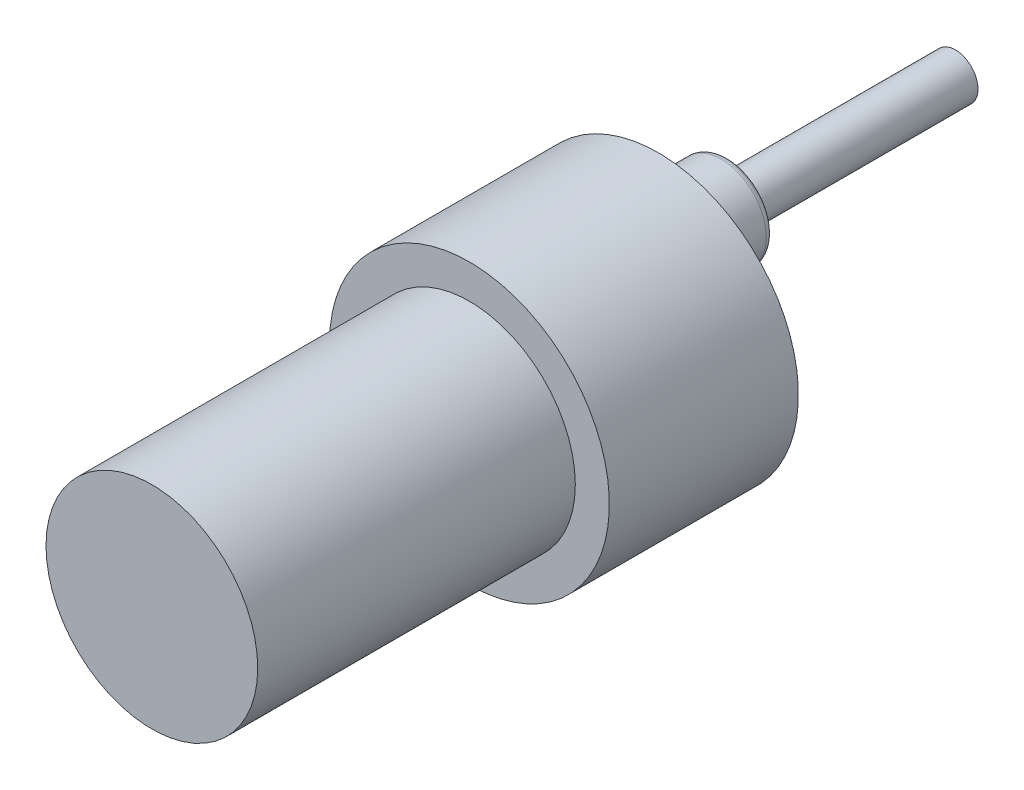
SolidWorks part; units mm, degrees
ref_plane "Front Plane" through (0, 0, 0) normal (0, 0, 1) x (1, 0, 0)
ref_plane "Top Plane" through (0, 0, 0) normal (0, 1, 0) x (1, 0, 0)
ref_plane "Right Plane" through (0, 0, 0) normal (1, 0, 0) x (0, 0, -1)
ref_plane "Plane1" through (0, 0, 0) normal (0, -1, 0) x (1, 0, 0)
sketch "Sketch1" plane through (0, 0, 0) normal (0, -1, 0) x (1, 0, 0)
  line L0 (18.5, 0) -> (0, 0)
  line L1 (0, 0) -> (0, -25)
  line L2 (0, -25) -> (18.5, -25)
  line L3 (18.5, -25) -> (18.5, 0)
  line L4 (0, 0) -> (0, -25) construction
revolve "Revolve1" add sketch "Sketch1" angle 360 about L4
sketch "Sketch2" plane through (0, 0, 0) normal (0, 0, 1) x (1, 0, 0)
  circle A0 centre (0, 0) radius 14
extrude "Boss-Extrude1" add sketch "Sketch2" along normal blind 42
ref_plane "Plane2" through (0, 7.419, 0) normal (0, -1, 0) x (1, 0, 0)
sketch "Sketch3" plane through (0, 7.419, 0) normal (0, -1, 0) x (1, 0, 0)
  line L0 (5.7577, -25) -> (-0.2423, -25)
  line L1 (-0.2423, -25) -> (-0.2423, -64.5)
  line L2 (-0.2423, -64.5) -> (2.7577, -64.5)
  line L3 (2.7577, -64.5) -> (2.7577, -34.5)
  line L4 (2.7577, -34.5) -> (5.7577, -34.5)
  line L5 (5.7577, -34.5) -> (5.7577, -25)
  line L6 (-0.2423, -25) -> (-0.2423, -64.5) construction
revolve "Revolve2" add sketch "Sketch3" angle 360 about L6
fillet "Fillet1" radius 1 1 edges at (-6.2423, 7.419, -34.5)
